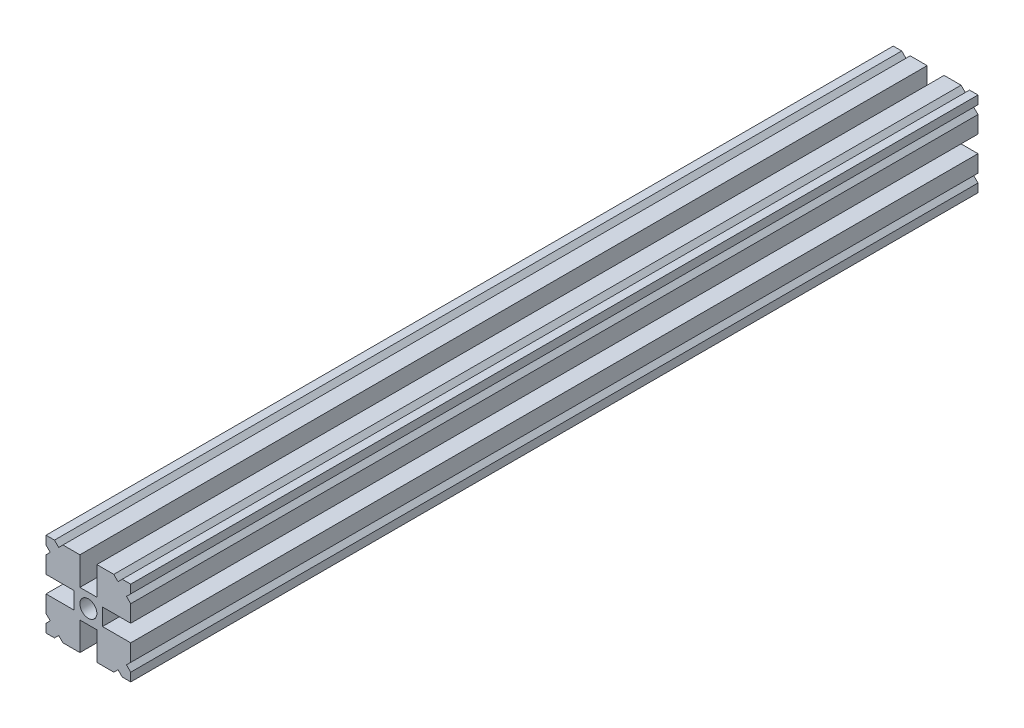
SolidWorks part; units mm, degrees
ref_plane "Front Plane" through (0, 0, 0) normal (0, 0, 1) x (1, 0, 0)
ref_plane "Top Plane" through (0, 0, 0) normal (0, 1, 0) x (1, 0, 0)
ref_plane "Right Plane" through (0, 0, 0) normal (1, 0, 0) x (0, 0, -1)
sketch "Sketch1" plane through (0, 0, 0) normal (0, 0, 1) x (1, 0, 0)
  line L0 (-1.5, 7.5) -> (1.5, 7.5) construction
  line L1 (-7.5, 7.5) -> (7.5, 7.5) construction
  line L2 (-7.5, 7.5) -> (-7.5, -7.5) construction
  line L3 (-7.5, -7.5) -> (7.5, -7.5) construction
  line L4 (7.5, 7.5) -> (7.5, -7.5) construction
  line L5 (-7.5, 7.5) -> (7.5, -7.5) construction
  line L6 (-7.5, -7.5) -> (7.5, 7.5) construction
  line L7 (-7.5, 7.5) -> (-6, 7.5)
  line L8 (7.5, 7.5) -> (6, 7.5)
  line L9 (-6, 7.5) -> (-5.25, 6.75)
  line L10 (-5.25, 6.75) -> (-4.5, 7.5)
  line L11 (-4.5, 7.5) -> (-1.5, 7.5)
  line L12 (-1.5, 7.5) -> (-1.5, 2.5)
  line L13 (-1.5, 2.5) -> (1.5, 2.5)
  line L14 (1.5, 2.5) -> (1.5, 7.5)
  line L15 (1.5, 7.5) -> (4.5, 7.5)
  line L16 (4.5, 7.5) -> (5.25, 6.75)
  line L17 (5.25, 6.75) -> (6, 7.5)
  line L18 (7.5, 7.5) -> (7.5, 6)
  line L19 (7.5, 6) -> (6.75, 5.25)
  line L20 (6.75, 5.25) -> (7.5, 4.5)
  line L21 (7.5, 4.5) -> (7.5, 1.5)
  line L22 (7.5, 1.5) -> (2.5, 1.5)
  line L23 (2.5, 1.5) -> (2.5, -1.5)
  line L24 (2.5, -1.5) -> (7.5, -1.5)
  line L25 (7.5, -1.5) -> (7.5, -4.5)
  line L26 (6.75, -5.25) -> (7.5, -6)
  line L27 (7.5, -4.5) -> (6.75, -5.25)
  line L28 (7.5, -7.5) -> (7.5, -6)
  line L29 (7.5, -7.5) -> (6, -7.5)
  line L30 (6, -7.5) -> (5.25, -6.75)
  line L31 (5.25, -6.75) -> (4.5, -7.5)
  line L32 (4.5, -7.5) -> (1.5, -7.5)
  line L33 (1.5, -7.5) -> (1.5, -2.5)
  line L34 (1.5, -2.5) -> (-1.5, -2.5)
  line L35 (-1.5, -2.5) -> (-1.5, -7.5)
  line L36 (-1.5, -7.5) -> (-4.5, -7.5)
  line L37 (-5.25, -6.75) -> (-6, -7.5)
  line L38 (-4.5, -7.5) -> (-5.25, -6.75)
  line L39 (-7.5, -7.5) -> (-6, -7.5)
  line L40 (-7.5, -7.5) -> (-7.5, -6)
  line L41 (-7.5, -6) -> (-6.75, -5.25)
  line L42 (-6.75, -5.25) -> (-7.5, -4.5)
  line L43 (-7.5, -4.5) -> (-7.5, -1.5)
  line L44 (-7.5, -1.5) -> (-2.5, -1.5)
  line L45 (-2.5, -1.5) -> (-2.5, 1.5)
  line L46 (-2.5, 1.5) -> (-7.5, 1.5)
  line L47 (-7.5, 1.5) -> (-7.5, 4.5)
  line L48 (-6.75, 5.25) -> (-7.5, 6)
  line L49 (-7.5, 4.5) -> (-6.75, 5.25)
  line L50 (-7.5, 7.5) -> (-7.5, 6)
  circle A0 centre (0, 0) radius 1.5
  point P0 (0, 0)
  point P8 (0, 7.5)
  point P56 (0, 0)
  dimension "D8" = 3
  dimension "D1" = 15
  dimension "D2" = 3
  dimension "D3" = 1.5
  dimension "D4" = 5
  dimension "D5" = 1.5
  dimension "D6" = 3
  dimension "D7" = 4
extrude "Boss-Extrude1" add sketch "Sketch1" along normal blind 150
move or copy body "Body-Move/Copy1" [suppressed] bodies to move or copy 101
